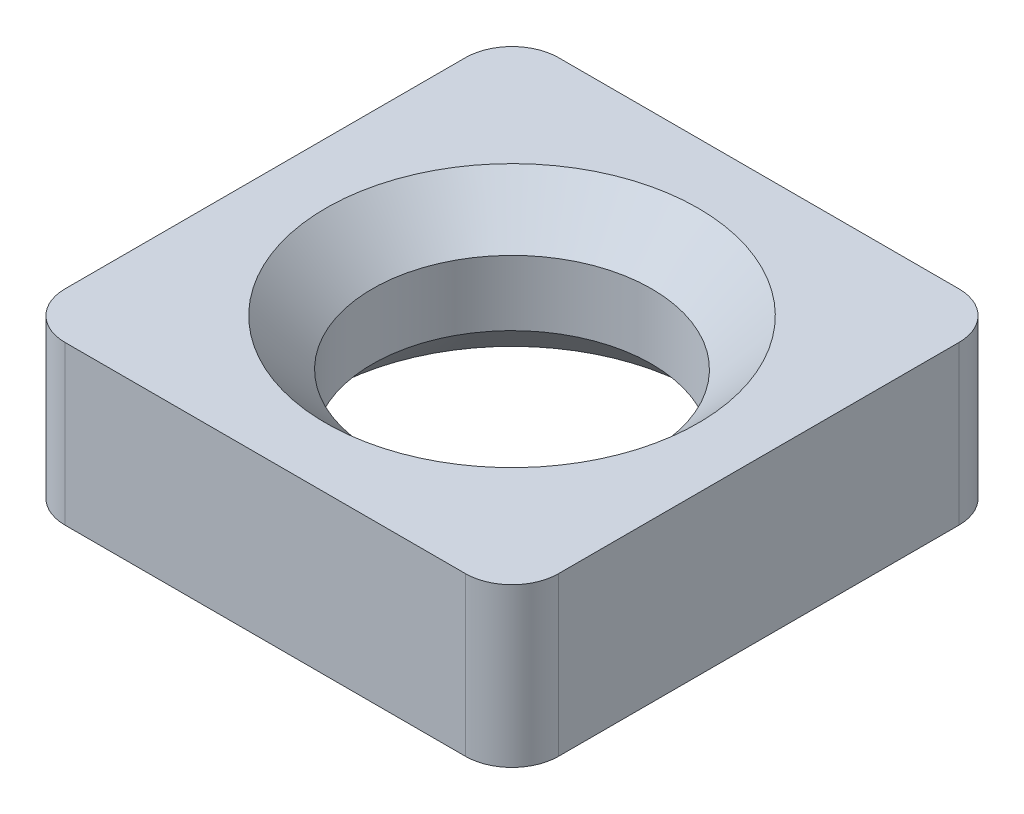
SolidWorks part; units mm, degrees
material "AISI 304"
ref_plane "Front Plane" through (0, 0, 0) normal (0, 0, 1) x (1, 0, 0)
ref_plane "Top Plane" through (0, 0, 0) normal (0, 1, 0) x (1, 0, 0)
ref_plane "Right Plane" through (0, 0, 0) normal (1, 0, 0) x (0, 0, -1)
sketch "Sketch1" plane through (0, 0, 0) normal (0, 1, 0) x (1, 0, 0)
  line L1 (-2.65, -2.65) -> (2.65, -2.65)
  line L2 (-2.65, -2.65) -> (-2.65, 2.65)
  line L3 (-2.65, 2.65) -> (2.65, 2.65)
  line L4 (2.65, -2.65) -> (2.65, 2.65)
  line L5 (-2.65, -2.65) -> (2.65, 2.65) construction
  line L6 (-2.65, 2.65) -> (2.65, -2.65) construction
  circle A0 centre (0, 0) radius 1.5
  point P0 (0, 0)
  dimension "D2" = 3
  dimension "D1" = 5.3
extrude "Boss-Extrude1" add sketch "Sketch1" along normal blind 1.7
fillet "Fillet1" radius 0.5 4 edges at (-2.65, 0.85, -2.65) (-2.65, 0.85, 2.65) (2.65, 0.85, -2.65) (2.65, 0.85, 2.65)
chamfer "Chamfer1" distance 0.5 angle 45 2 edges at (0, 0, 1.5) (0, 1.7, 1.5)
